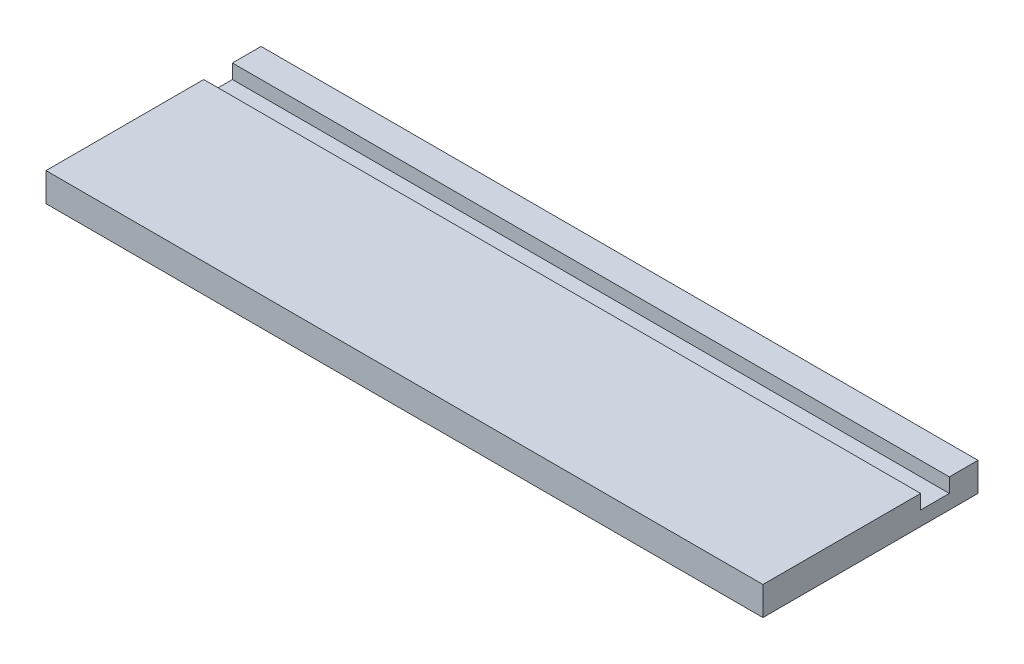
SolidWorks part; units mm, degrees
ref_plane "Plan de face" through (0, 0, 0) normal (0, 0, 1) x (1, 0, 0)
ref_plane "Plan de dessus" through (0, 0, 0) normal (0, 1, 0) x (1, 0, 0)
ref_plane "Plan de droite" through (0, 0, 0) normal (1, 0, 0) x (0, 0, -1)
sketch "Esquisse1" plane through (0, 0, 0) normal (0, 1, 0) x (1, 0, 0)
  line L1 (-250, 75) -> (250, 75)
  line L2 (-250, 75) -> (-250, -75)
  line L3 (-250, -75) -> (250, -75)
  line L4 (250, 75) -> (250, -75)
  line L5 (-250, 75) -> (250, -75) construction
  line L6 (-250, -75) -> (250, 75) construction
  point P0 (0, 0)
  dimension "D1" = 500
  dimension "D2" = 150
extrude "Boss.-Extru.1" add sketch "Esquisse1" along normal blind 20
sketch "Esquisse2" plane through (0, 20, 0) normal (0, 1, 0) x (1, 0, 0)
  line L0 (-250, 75) -> (-250, -75) construction
  line L1 (-250, 55) -> (250, 55)
  line L2 (-250, 55) -> (-250, 35)
  line L3 (-250, 35) -> (250, 35)
  line L4 (250, 55) -> (250, 35)
  line L5 (250, -75) -> (250, 75) construction
  line L6 (250, 75) -> (-250, 75) construction
  dimension "D1" = 20
  dimension "D2" = 20
extrude "Enlèv. mat.-Extru.1" cut sketch "Esquisse2" against normal blind 10
